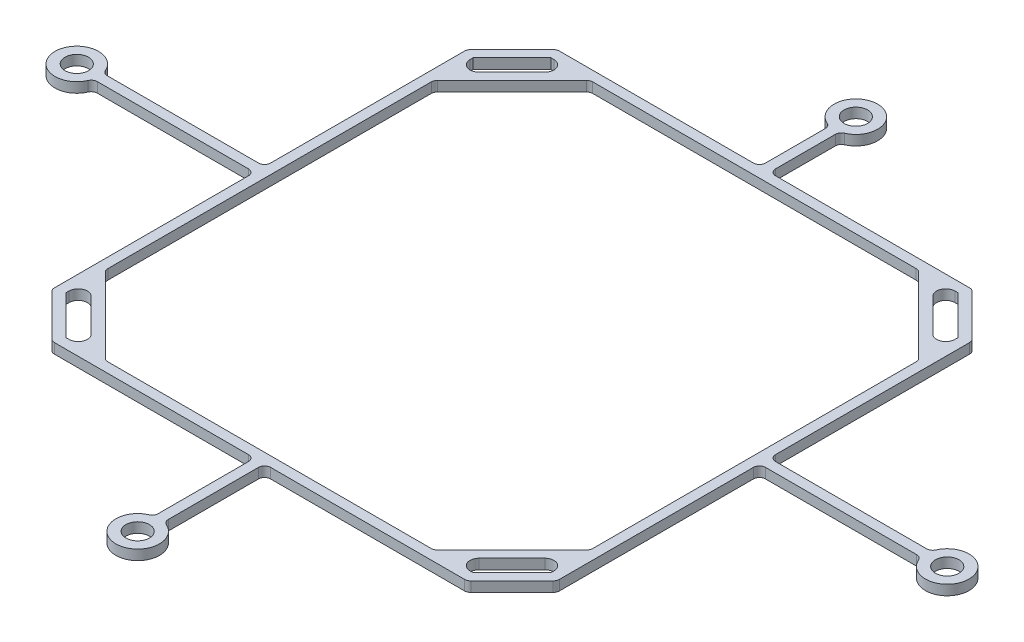
SolidWorks part; units mm, degrees
ref_plane "Front Plane" through (0, 0, 0) normal (0, 0, 1) x (1, 0, 0)
ref_plane "Top Plane" through (0, 0, 0) normal (0, 1, 0) x (1, 0, 0)
ref_plane "Right Plane" through (0, 0, 0) normal (1, 0, 0) x (0, 0, -1)
sketch "Sketch1" plane through (0, 0, 0) normal (0, 1, 0) x (1, 0, 0)
  line L0 (0, 0) -> (0, 56.4488) construction
  line L1 (0, 0) -> (-71.4488, 0) construction
  line L2 (-39.7988, 33.4083) -> (-33.4083, 39.7988)
  line L3 (-33.4083, -39.7988) -> (-29.2929, -39.7988)
  line L4 (-39.7988, -33.4083) -> (-39.7988, -29.2929)
  line L5 (-33.4083, 39.7988) -> (-29.2929, 39.7988)
  line L6 (39.7988, -33.4083) -> (39.7988, -29.2929)
  line L7 (-39.7988, -39.7988) -> (36.6035, 36.6035) construction
  line L8 (-36.6035, 36.6035) -> (39.7988, -39.7988) construction
  line L9 (33.4083, 39.7988) -> (39.7988, 33.4083)
  line L10 (39.7988, -33.4083) -> (33.4083, -39.7988)
  line L11 (-33.4083, -39.7988) -> (-39.7988, -33.4083)
  line L12 (-41.4488, 34.0917) -> (-34.0917, 41.4488)
  line L13 (34.0917, 41.4488) -> (0.825, 41.4488)
  line L14 (34.0917, 41.4488) -> (41.4488, 34.0917)
  line L15 (41.4488, -34.0917) -> (41.4488, -0.825)
  line L16 (41.4488, -34.0917) -> (34.0917, -41.4488)
  line L17 (-34.0917, -41.4488) -> (-0.825, -41.4488)
  line L18 (-34.0917, -41.4488) -> (-41.4488, -34.0917)
  line L19 (-41.4488, 34.0917) -> (-41.4488, 0.825)
  line L20 (-39.7988, 29.2929) -> (-29.2929, 39.7988)
  line L21 (-39.7988, 26.9594) -> (-26.9594, 39.7988)
  line L22 (29.2929, 39.7988) -> (39.7988, 29.2929)
  line L23 (26.9594, 39.7988) -> (39.7988, 26.9594)
  line L24 (39.7988, -29.2929) -> (29.2929, -39.7988)
  line L25 (39.7988, -26.9594) -> (26.9594, -39.7988)
  line L26 (-29.2929, -39.7988) -> (-39.7988, -29.2929)
  line L27 (-26.9594, -39.7988) -> (-39.7988, -26.9594)
  line L28 (-39.7988, 29.2929) -> (-39.7988, 33.4083)
  line L29 (-26.9594, 39.7988) -> (26.9594, 39.7988)
  line L30 (29.2929, 39.7988) -> (33.4083, 39.7988)
  line L31 (39.7988, 29.2929) -> (39.7988, 33.4083)
  line L32 (39.7988, -26.9594) -> (39.7988, 26.9594)
  line L33 (-39.7988, -26.9594) -> (-39.7988, 26.9594)
  line L34 (-26.9594, -39.7988) -> (26.9594, -39.7988)
  line L35 (29.2929, -39.7988) -> (33.4083, -39.7988)
  line L36 (67.9703, -0.825) -> (41.4488, -0.825)
  line L37 (0.825, 52.9703) -> (0.825, 41.4488)
  line L38 (-0.825, 52.9703) -> (-0.825, 41.4488)
  line L39 (67.9703, 0.825) -> (41.4488, 0.825)
  line L40 (-0.825, -57.9703) -> (-0.825, -41.4488)
  line L41 (0.825, -57.9703) -> (0.825, -41.4488)
  line L42 (-67.9703, 0.825) -> (-41.4488, 0.825)
  line L43 (-67.9703, -0.825) -> (-41.4488, -0.825)
  line L44 (0, 0) -> (0, -61.4488) construction
  line L45 (41.4488, 0.825) -> (41.4488, 34.0917)
  line L46 (-0.825, 41.4488) -> (-34.0917, 41.4488)
  line L47 (-41.4488, -0.825) -> (-41.4488, -34.0917)
  line L48 (0.825, -41.4488) -> (34.0917, -41.4488)
  arc A0 (0.825, 52.9703) -> (-0.825, 52.9703) centre (0, 56.4488) ccw
  circle A1 centre (0, 56.4488) radius 1.925
  circle A2 centre (71.4488, 0) radius 1.925
  arc A3 (67.9703, 0.825) -> (67.9703, -0.825) centre (71.4488, 0) cw
  arc A4 (-0.825, -57.9703) -> (0.825, -57.9703) centre (0, -61.4488) ccw
  circle A5 centre (0, -61.4488) radius 1.925
  arc A6 (-67.9703, 0.825) -> (-67.9703, -0.825) centre (-71.4488, 0) ccw
  circle A7 centre (-71.4488, 0) radius 1.925
  point P19 (0, 0)
  point P20 (0, 0)
  point P28 (-305.6096, 132.6723)
  point P33 (0, 0)
  point P46 (0, 0)
  point P74 (0, 0)
  dimension "D10" = 3.85
  dimension "D11" = 1.65
  dimension "D15" = 1.65
  dimension "D16" = 3.85
  dimension "D20" = 3.85
  dimension "D21" = 1.65
  dimension "D1" = 1.65
  dimension "D2" = 79.5976
  dimension "D3" = 9.0376
  dimension "D5" = 1.65
  dimension "D6" = 4
  dimension "D7" = 2.91
  dimension "D8" = 1.65
  dimension "D12" = 0.825
  dimension "D13" = 0.825
  dimension "D14" = 15
  dimension "D17" = 30
  dimension "D18" = 0.825
  dimension "D19" = 0.825
  dimension "D22" = 0.825
  dimension "D23" = 0.825
  dimension "D24" = 20
  dimension "D4" = 4
  dimension "D9" = 4
extrude "Boss-Extrude1" add sketch "Sketch1" along normal blind 1.65
fillet "Fillet4" radius 1 16 edges at (0.825, 0.825, -41.4488) (0.825, 0.825, -52.9703) (-0.825, 0.825, -52.9703) (-0.825, 0.825, -41.4488) (67.9703, 0.825, -0.825) (67.9703, 0.825, 0.825) (41.4488, 0.825, -0.825) (41.4488, 0.825, 0.825) (0.825, 0.825, 57.9703) (-0.825, 0.825, 57.9703) (-0.825, 0.825, 41.4488) (0.825, 0.825, 41.4488) (-41.4488, 0.825, 0.825) (-41.4488, 0.825, -0.825) (-67.9703, 0.825, 0.825) (-67.9703, 0.825, -0.825)
fillet "Fillet3" radius 1.5 8 edges at (29.2929, 0.825, 39.7988) (39.7988, 0.825, 29.2929) (-29.2929, 0.825, 39.7988) (-39.7988, 0.825, 29.2929) (-39.7988, 0.825, -29.2929) (-29.2929, 0.825, -39.7988) (39.7988, 0.825, -29.2929) (29.2929, 0.825, -39.7988)
fillet "Fillet5" radius 1 16 edges at (-26.9594, 0.825, 39.7988) (-39.7988, 0.825, 26.9594) (-41.4488, 0.825, 34.0917) (-34.0917, 0.825, 41.4488) (-39.7988, 0.825, -26.9594) (-26.9594, 0.825, -39.7988) (-41.4488, 0.825, -34.0917) (-34.0917, 0.825, -41.4488) (41.4488, 0.825, -34.0917) (34.0917, 0.825, -41.4488) (26.9594, 0.825, -39.7988) (39.7988, 0.825, -26.9594) (34.0917, 0.825, 41.4488) (41.4488, 0.825, 34.0917) (39.7988, 0.825, 26.9594) (26.9594, 0.825, 39.7988)
